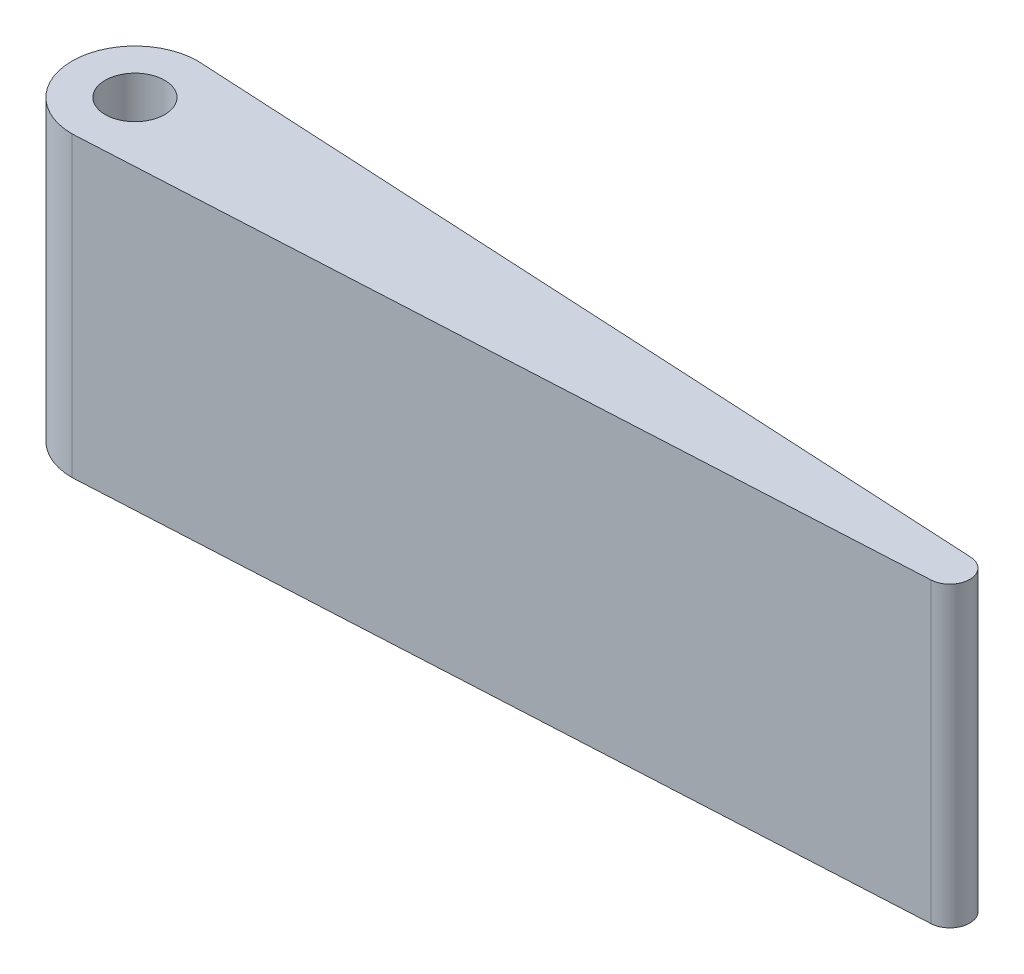
SolidWorks part; units mm, degrees
ref_plane "Front Plane" through (0, 0, 0) normal (0, 0, 1) x (1, 0, 0)
ref_plane "Top Plane" through (0, 0, 0) normal (0, 1, 0) x (1, 0, 0)
ref_plane "Right Plane" through (0, 0, 0) normal (1, 0, 0) x (0, 0, -1)
sketch "Sketch1" plane through (0, 0, 0) normal (0, 1, 0) x (1, 0, 0)
  line L0 (0, 0) -> (120, 0) construction
  line L1 (120, 0) -> (-0.0162, 6.3469)
  line L2 (120, 0) -> (0.0162, -6.3469)
  circle A0 centre (0, 0) radius 3
  arc A1 (-0.0162, 6.3469) -> (0.0162, -6.3469) centre (0, 0) ccw
  point P4 (0, 0)
  dimension "D2" = 6
  dimension "D3" = 6.3469
  dimension "D1" = 120
extrude "Boss-Extrude1" add sketch "Sketch1" along normal blind 30
fillet "Fillet1" radius 2 1 edges at (120, 15, 0)
